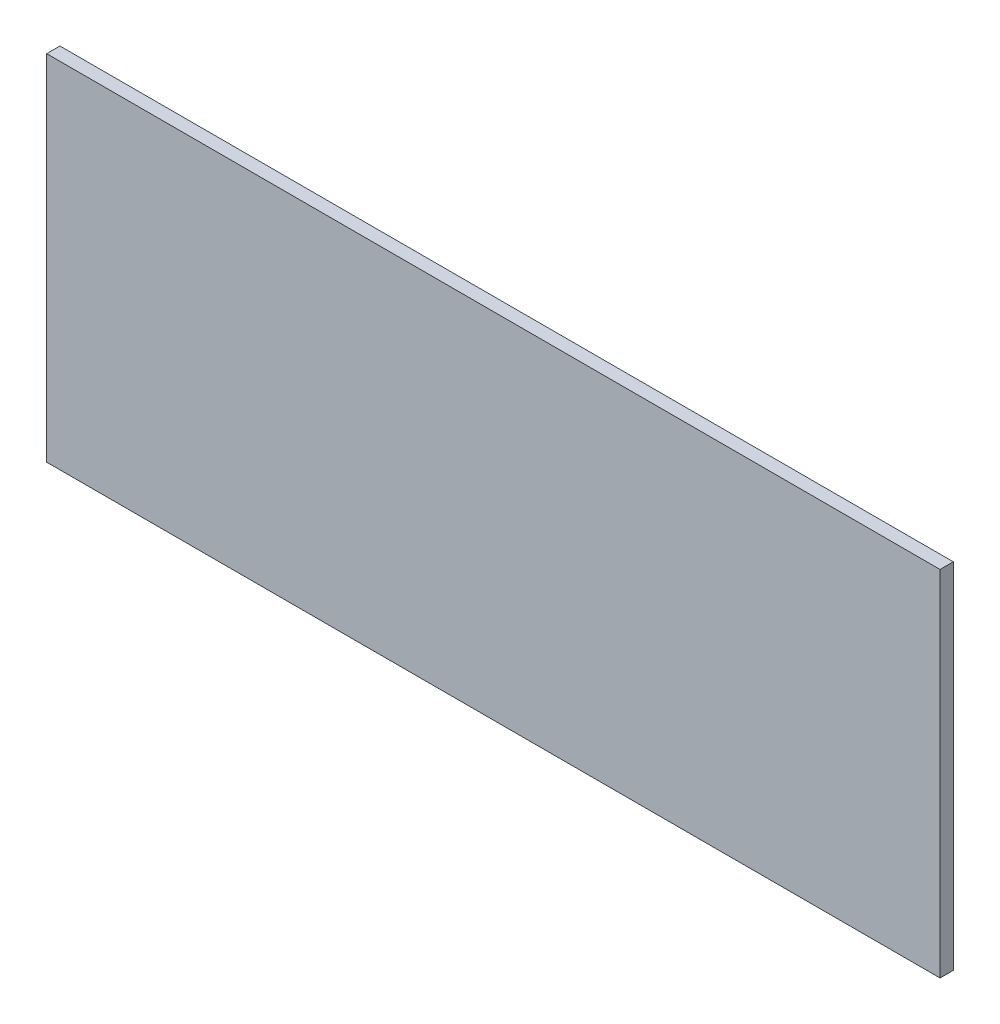
SolidWorks part; units mm, degrees
ref_plane "Спереди" through (0, 0, 0) normal (0, 0, 1) x (1, 0, 0)
ref_plane "Сверху" through (0, 0, 0) normal (0, 1, 0) x (1, 0, 0)
ref_plane "Справа" through (0, 0, 0) normal (1, 0, 0) x (0, 0, -1)
sketch "Эскиз1" plane through (0, 0, 0) normal (0, 0, 1) x (1, 0, 0)
  line L1 (-50.5, -20) -> (50.5, -20)
  line L2 (-50.5, -20) -> (-50.5, 20)
  line L3 (-50.5, 20) -> (50.5, 20)
  line L4 (50.5, -20) -> (50.5, 20)
  line L6 (-50.5, -20) -> (50.5, 20) construction
  line L7 (-50.5, 20) -> (50.5, -20) construction
  dimension "D1" = 101
  dimension "D2" = 40
extrude "Бобышка-Вытянуть1" add sketch "Эскиз1" along normal blind 1.5
